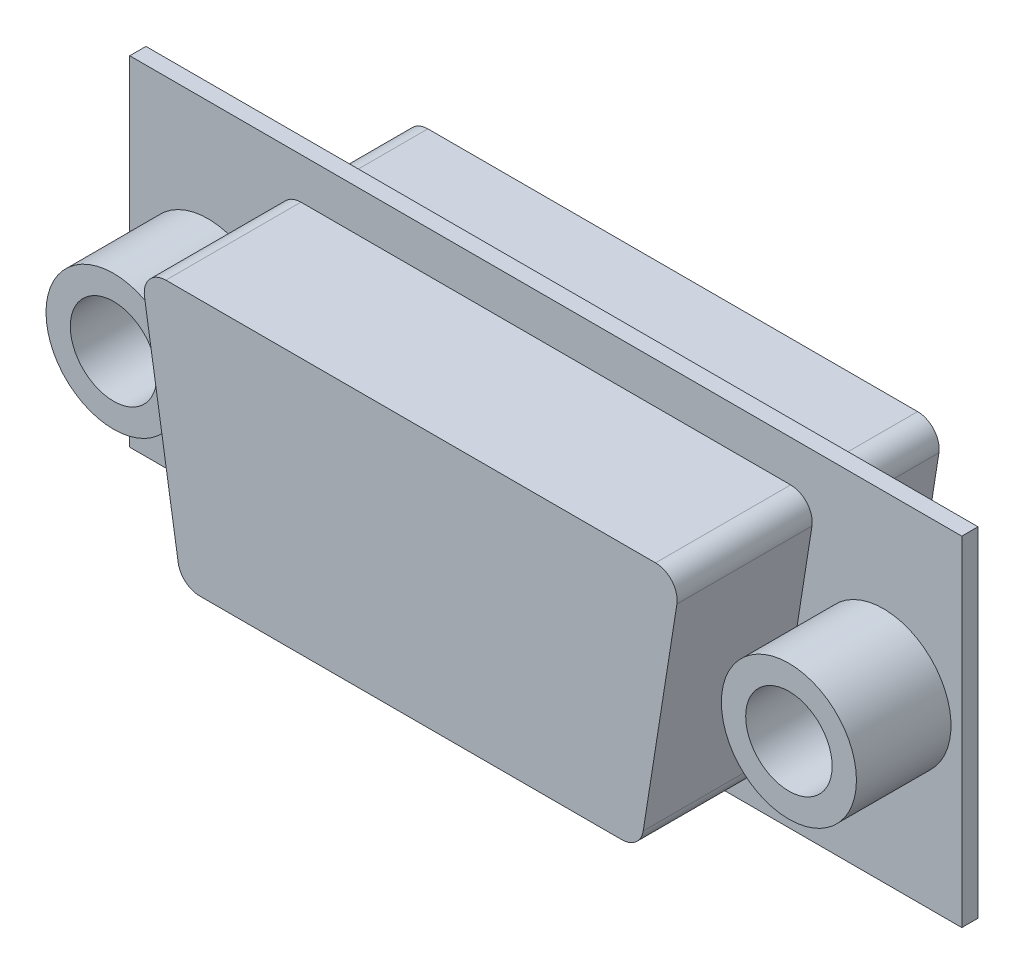
SolidWorks part; units mm, degrees
ref_plane "前视基准面" through (0, 0, 0) normal (0, 0, 1) x (1, 0, 0)
ref_plane "上视基准面" through (0, 0, 0) normal (0, 1, 0) x (1, 0, 0)
ref_plane "右视基准面" through (0, 0, 0) normal (1, 0, 0) x (0, 0, -1)
other "Configuration Table"
sketch "草图1" plane through (0, 0, 0) normal (0, 0, 1) x (1, 0, 0)
  line L0 (-9.0638, 4.75) -> (9.0638, 4.75)
  line L1 (9.854, 3.8252) -> (8.6066, -4.0748)
  line L2 (7.8164, -4.75) -> (-7.8164, -4.75)
  line L3 (-8.6066, -4.0748) -> (-9.854, 3.8252)
  arc A0 (-9.854, 3.8252) -> (-9.0638, 4.75) centre (-9.0638, 3.95) cw
  arc A1 (9.0638, 4.75) -> (9.854, 3.8252) centre (9.0638, 3.95) cw
  arc A2 (8.6066, -4.0748) -> (7.8164, -4.75) centre (7.8164, -3.95) cw
  arc A3 (-7.8164, -4.75) -> (-8.6066, -4.0748) centre (-7.8164, -3.95) cw
extrude "F3_01_ContinuousSocketBody_D9.70" add sketch "草图1" along normal blind 9.7
sketch "草图2" plane through (0, 0, 0) normal (0, 0, 1) x (1, 0, 0)
  line L1 (-15.4, -6.275) -> (15.4, -6.275)
  line L2 (-15.4, -6.275) -> (-15.4, 6.275)
  line L3 (-15.4, 6.275) -> (15.4, 6.275)
  line L4 (15.4, -6.275) -> (15.4, 6.275)
  line L5 (-15.4, -6.275) -> (15.4, 6.275) construction
  line L6 (-15.4, 6.275) -> (15.4, -6.275) construction
extrude "F3_02_FlangeBlank_ToZ4.70" add sketch "草图2" along normal blind 4.7
sketch "草图3" plane through (0, 0, 0) normal (0, 0, 1) x (1, 0, 0)
  circle A0 centre (-12.5, 0) radius 2.5
  circle A1 centre (12.5, 0) radius 2.5
extrude "F3_03_FixedPostBlank_ToZ8.20" add sketch "草图3" along normal blind 8.2
sketch "草图4" plane through (0, 0, 0) normal (0, 0, 1) x (1, 0, 0)
  line L1 (-15.4, -6.275) -> (15.4, -6.275)
  line L2 (-15.4, -6.275) -> (-15.4, 6.275)
  line L3 (-15.4, 6.275) -> (15.4, 6.275)
  line L4 (15.4, -6.275) -> (15.4, 6.275)
  line L5 (-15.4, -6.275) -> (15.4, 6.275) construction
  line L6 (-15.4, 6.275) -> (15.4, -6.275) construction
  point P0 (0, 0)
extrude "F3_04_FrontRelief_ToZ4.10" cut sketch "草图4" along normal blind 4.1
sketch "草图5" plane through (0, 0, 0) normal (0, 0, 1) x (1, 0, 0)
  line L0 (-9.0638, 4.75) -> (9.0638, 4.75)
  line L1 (9.854, 3.8252) -> (8.6066, -4.0748)
  line L2 (7.8164, -4.75) -> (-7.8164, -4.75)
  line L3 (-8.6066, -4.0748) -> (-9.854, 3.8252)
  arc A0 (-9.854, 3.8252) -> (-9.0638, 4.75) centre (-9.0638, 3.95) cw
  arc A1 (9.0638, 4.75) -> (9.854, 3.8252) centre (9.0638, 3.95) cw
  arc A2 (8.6066, -4.0748) -> (7.8164, -4.75) centre (7.8164, -3.95) cw
  arc A3 (-7.8164, -4.75) -> (-8.6066, -4.0748) centre (-7.8164, -3.95) cw
extrude "F3_05_RestoreProtrudingSocketNose" add sketch "草图5" along normal blind 4.2
sketch "草图6" plane through (0, 0, 0) normal (0, 0, 1) x (1, 0, 0)
  line L0 (-7.444, 4.3) -> (7.444, 4.3)
  line L1 (8.3166, 3.1793) -> (6.5968, -3.6207)
  line L2 (5.7243, -4.3) -> (-5.7243, -4.3)
  line L3 (-6.5968, -3.6207) -> (-8.3166, 3.1793)
  arc A0 (-8.3166, 3.1793) -> (-7.444, 4.3) centre (-7.444, 3.4) cw
  arc A1 (7.444, 4.3) -> (8.3166, 3.1793) centre (7.444, 3.4) cw
  arc A2 (6.5968, -3.6207) -> (5.7243, -4.3) centre (5.7243, -3.4) cw
  arc A3 (-5.7243, -4.3) -> (-6.5968, -3.6207) centre (-5.7243, -3.4) cw
extrude "F3_06_DReceiverOuterPocket_D4.10" cut sketch "草图6" along normal blind 4.1
sketch "草图7" plane through (0, 0, 0) normal (0, 0, 1) x (1, 0, 0)
  line L0 (-7.047, 3.3) -> (7.047, 3.3)
  line L1 (7.4269, 2.7748) -> (5.5156, -3.0252)
  line L2 (5.1357, -3.3) -> (-5.1357, -3.3)
  line L3 (-5.5156, -3.0252) -> (-7.4269, 2.7748)
  arc A0 (-7.4269, 2.7748) -> (-7.047, 3.3) centre (-7.047, 2.9) cw
  arc A1 (7.047, 3.3) -> (7.4269, 2.7748) centre (7.047, 2.9) cw
  arc A2 (5.5156, -3.0252) -> (5.1357, -3.3) centre (5.1357, -2.9) cw
  arc A3 (-5.1357, -3.3) -> (-5.5156, -3.0252) centre (-5.1357, -2.9) cw
extrude "F3_07_DReceiverInnerIsland" add sketch "草图7" along normal blind 4.2
sketch "草图8" plane through (0, 0, 0) normal (0, 0, 1) x (1, 0, 0)
  circle A0 centre (-5.54, 1.42) radius 0.575
  circle A1 centre (-2.77, 1.42) radius 0.575
  circle A2 centre (0, 1.42) radius 0.575
  circle A3 centre (2.77, 1.42) radius 0.575
  circle A4 centre (5.54, 1.42) radius 0.575
  circle A5 centre (-4.155, -1.42) radius 0.575
  circle A6 centre (-1.385, -1.42) radius 0.575
  circle A7 centre (1.385, -1.42) radius 0.575
  circle A8 centre (4.155, -1.42) radius 0.575
extrude "F3_08_9ContactHoles_Dia1.15_D4.50" cut sketch "草图8" along normal blind 4.5
sketch "草图9" plane through (0, 0, 0) normal (0, 0, 1) x (1, 0, 0)
  circle A0 centre (-5.54, 1.42) radius 0.675
  circle A1 centre (-2.77, 1.42) radius 0.675
  circle A2 centre (0, 1.42) radius 0.675
  circle A3 centre (2.77, 1.42) radius 0.675
  circle A4 centre (5.54, 1.42) radius 0.675
  circle A5 centre (-4.155, -1.42) radius 0.675
  circle A6 centre (-1.385, -1.42) radius 0.675
  circle A7 centre (1.385, -1.42) radius 0.675
  circle A8 centre (4.155, -1.42) radius 0.675
extrude "F3_09_EquivalentLeadIn_Dia1.35_D0.25" cut sketch "草图9" along normal blind 0.25
sketch "草图10" plane through (0, 0, 0) normal (0, 0, 1) x (1, 0, 0)
  circle A0 centre (-12.5, 0) radius 1.6
  circle A1 centre (12.5, 0) radius 1.6
extrude "F3_10_FixedPostBores_Dia3.20" cut sketch "草图10" along normal blind 8.3
